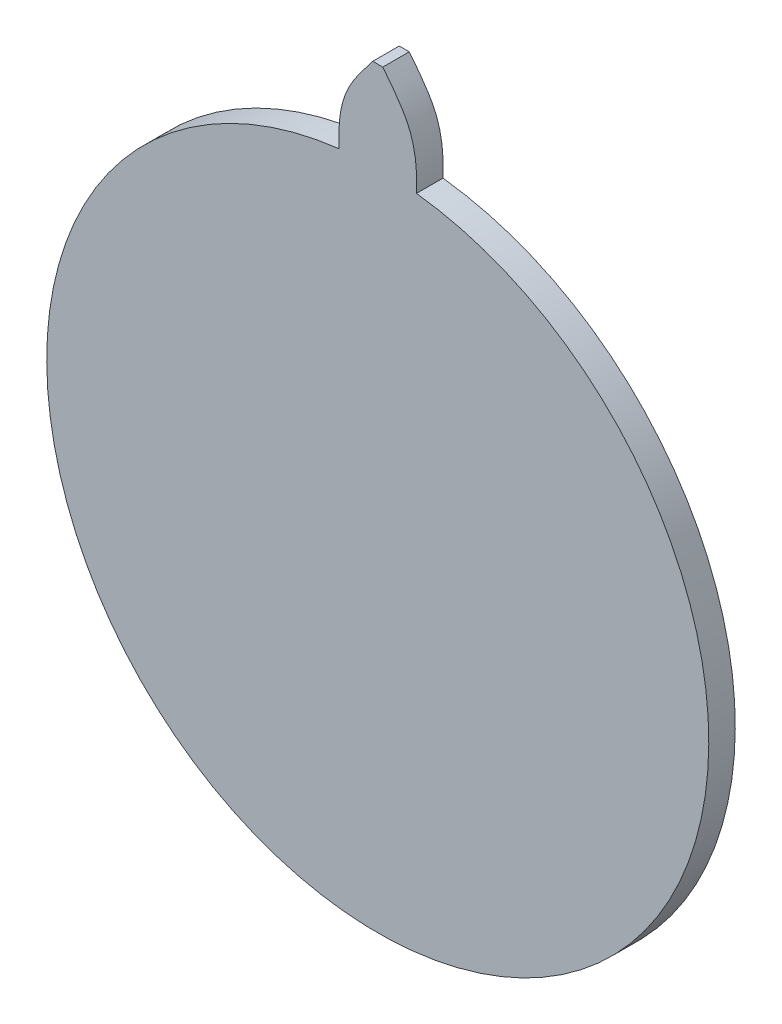
SolidWorks part; units mm, degrees
ref_plane "Front Plane" through (0, 0, 0) normal (0, 0, 1) x (1, 0, 0)
ref_plane "Top Plane" through (0, 0, 0) normal (0, 1, 0) x (1, 0, 0)
ref_plane "Right Plane" through (0, 0, 0) normal (1, 0, 0) x (0, 0, -1)
sketch "Sketch1" plane through (0, 0, 0) normal (0, 0, 1) x (1, 0, 0)
  circle A0 centre (0, 0) radius 34.9335
  dimension "D1" = 69.867
extrude "Boss-Extrude1" add sketch "Sketch1" along normal blind 2.794
sketch "Sketch2" plane through (0, 0, 0) normal (0, 0, 1) x (1, 0, 0)
  line L0 (0, 0) -> (0, 30.6991) construction
  line L1 (0, 30.6991) -> (0, 34.9335) construction
  line L2 (0, 34.9335) -> (0, 40.2265) construction
  line L3 (0, 40.2265) -> (0, 44.4608) construction
  line L4 (-0.5293, 44.4608) -> (0.5293, 44.4608)
  arc A1 (3.65, 30.4814) -> (-3.65, 30.4814) centre (0, 0) ccw
  spline S0 degree 3 poles (0.5293, 44.4608) (1.6115, 43.0971) (4.7731, 39.1133) (4.0956, 33.9061) (3.65, 30.4814) knots 0 0 0 0 0.3423 1 1 1 1
  spline S1 degree 3 poles (-0.5293, 44.4608) (-1.6115, 43.0971) (-4.7731, 39.1133) (-4.0956, 33.9061) (-3.65, 30.4814) knots 0 0 0 0 0.3423 1 1 1 1
  dimension "D1" = 34.9335
  dimension "D2" = 4.2344
  dimension "D3" = 5.293
  dimension "D4" = 4.2344
  dimension "D5" = 1.0586
  dimension "D6" = 5.3845
  dimension "D8" = 5.3845
  dimension "D9" = 6.2513
  dimension "D10" = 6.2513
  dimension "D7" = 7.3174
extrude "Boss-Extrude2" add sketch "Sketch2" along normal blind 2.794
